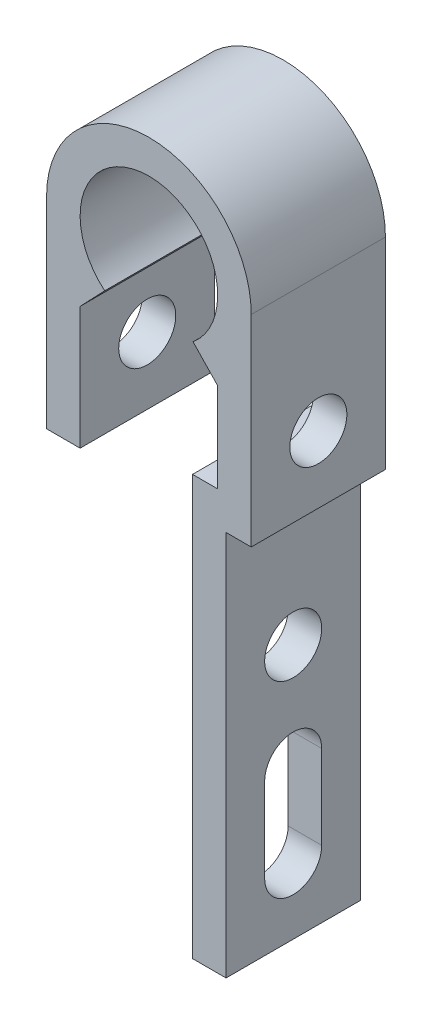
SolidWorks part; units mm, degrees
ref_plane "Plano frontal" through (0, 0, 0) normal (0, 0, 1) x (1, 0, 0)
ref_plane "Plano superior" through (0, 0, 0) normal (0, 1, 0) x (1, 0, 0)
ref_plane "Plano direito" through (0, 0, 0) normal (1, 0, 0) x (0, 0, -1)
sketch "Esboço1" plane through (0, 0, 0) normal (0, 0, 1) x (1, 0, 0)
  line L0 (4.1, -4.6769) -> (2.6354, -3.1408)
  line L1 (4.1, -4.6769) -> (4.1, -10)
  line L2 (4.1, -10) -> (2.6, -10)
  line L3 (2.6, -10) -> (2.6, -35)
  line L4 (-6.1, -12) -> (-6.1, 0)
  line L5 (6.1, 0) -> (6.1, -12)
  line L6 (6.1, -12) -> (4.6, -12)
  line L7 (4.6, -12) -> (4.6, -35)
  line L8 (-6.1, -12) -> (-4.1, -12)
  line L9 (2.6, -35) -> (4.6, -35)
  line L10 (2.6, -10) -> (-3.7, -10) construction
  line L11 (-3.7, -10) -> (-3.7, -35) construction
  line L12 (-3.7, -35) -> (2.6, -35) construction
  line L13 (-4.1, -12) -> (-4.1, -4.6769)
  line L14 (-2.6354, -3.1408) -> (-4.1, -4.6769)
  arc A0 (-2.6354, -3.1408) -> (2.6354, -3.1408) centre (0, 0) cw
  arc A1 (-6.1, 0) -> (6.1, 0) centre (0, 0) cw
  point P1 (-3.7, -8.5417)
  point P3 (4.1, -8.5417)
  point P19 (4.1, -6.1)
  point P21 (-3.7, -6.1)
  point P22 (5.2814, -12)
  point P23 (5.7733, -12)
  point P24 (-3.7, -5.7248)
  point P25 (0, 0)
  point P26 (-2.0548, -3.5535)
  point P27 (-2.6202, -3.128)
  point P28 (0, 0)
  point P29 (-4.1, -3.8822)
  point P30 (-3.7, -4.6769)
  dimension "D1" = 4.1
  dimension "D5" = 2
  dimension "D2" = 1.5
  dimension "D3" = 2
  dimension "D4" = 25
  dimension "D6" = 12
  dimension "D7" = 6.3
  dimension "D8" = 2
  dimension "D9" = 2
  dimension "D10" = 2
  dimension "D11" = 80
extrude "Ressalto-extrusão1" add sketch "Esboço1" along normal blind 8
sketch "Esboço2" plane through (-6.1, 0, 0) normal (-1, 0, 0) x (0, 0, 1)
  line L0 (4, -26) -> (4, -31) construction
  line L1 (5.7, -26) -> (5.7, -31)
  line L2 (2.3, -26) -> (2.3, -31)
  line L3 (8, -10) -> (0, -10) construction
  line L6 (8, -12) -> (0, -12) construction
  line L7 (0, 0) -> (0, -4.2) construction
  line L8 (0, 0) -> (0, -12) construction
  line L9 (0, -4.2) -> (8, -4.2) construction
  line L10 (8, 0) -> (8, -12) construction
  line L11 (8, -35) -> (0, -35) construction
  circle A0 centre (4, -8) radius 1.7
  circle A1 centre (4, -19.8) radius 1.7
  arc A2 (5.7, -26) -> (2.3, -26) centre (4, -26) ccw
  arc A3 (2.3, -31) -> (5.7, -31) centre (4, -31) ccw
  point P6 (4, -28.5)
  point P16 (4, -10)
  dimension "D1" = 7
  dimension "D2" = 3.4
  dimension "D3" = 5
  dimension "D4" = 4
  dimension "D5" = 4
  dimension "D6" = 4.2
extrude "Corte-extrusão1" cut sketch "Esboço2" against normal through all
